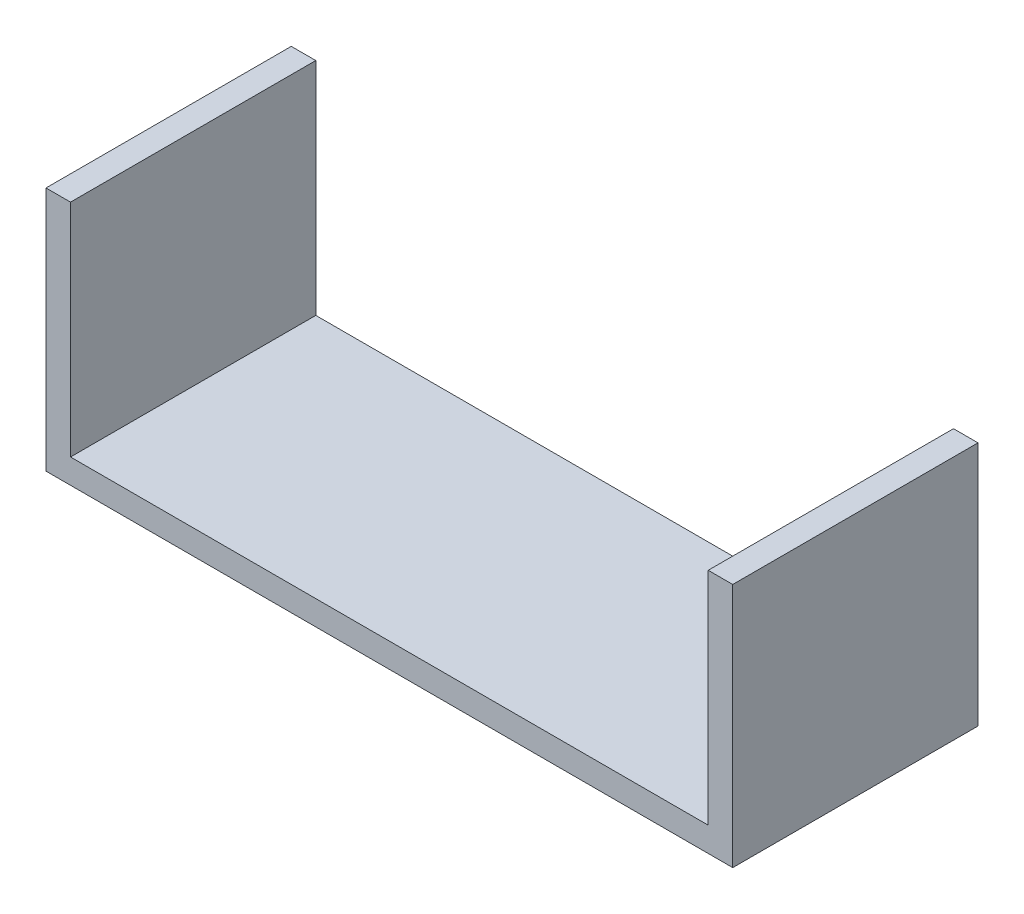
SolidWorks part; units mm, degrees
material "Papel canelado"
ref_plane "Plano frontal" through (0, 0, 0) normal (0, 0, 1) x (1, 0, 0)
ref_plane "Plano superior" through (0, 0, 0) normal (0, 1, 0) x (1, 0, 0)
ref_plane "Plano direito" through (0, 0, 0) normal (1, 0, 0) x (0, 0, -1)
sketch "Esboço1" plane through (0, 0, 0) normal (0, 0, 1) x (1, 0, 0)
  line L1 (0, 0) -> (140, 0)
  line L2 (0, 0) -> (0, 50)
  line L3 (0, 50) -> (140, 50)
  line L4 (140, 0) -> (140, 50)
  line L5 (5, 50) -> (135, 50)
  line L6 (5, 50) -> (5, 5)
  line L7 (5, 5) -> (135, 5)
  line L8 (135, 50) -> (135, 5)
  dimension "D1" = 5
  dimension "D2" = 5
  dimension "D3" = 5
  dimension "D4" = 140
  dimension "D5" = 50
extrude "Ressalto-extrusão1" add sketch "Esboço1" along normal blind 50 contours L3 L8 L7 L6 L2 L1 L4
